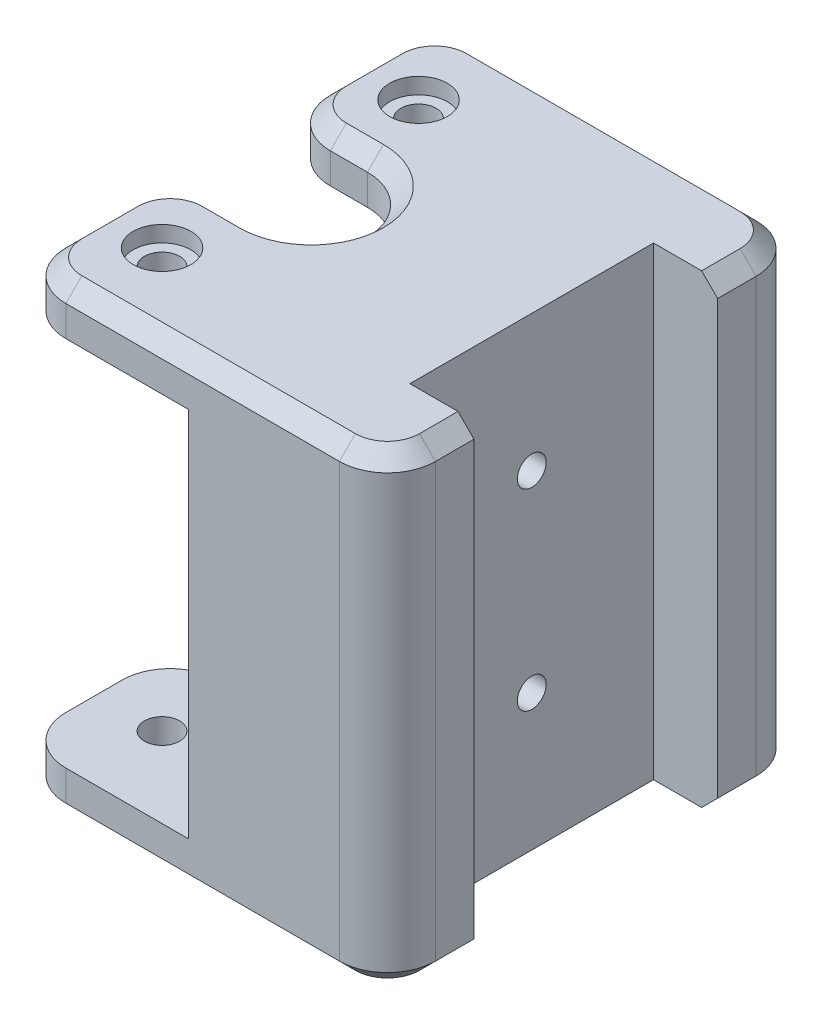
SolidWorks part; units mm, degrees
ref_plane "Спереди" through (0, 0, 0) normal (0, 0, 1) x (1, 0, 0)
ref_plane "Сверху" through (0, 0, 0) normal (0, 1, 0) x (1, 0, 0)
ref_plane "Справа" through (0, 0, 0) normal (1, 0, 0) x (0, 0, -1)
sketch "Эскиз2" plane through (0, 0, 0) normal (0, 1, 0) x (1, 0, 0)
  line L0 (23.6854, 8) -> (23.6854, -8) construction
  line L2 (19.6854, 13) -> (42.75, 13)
  line L3 (19.6854, 13) -> (19.6854, -13)
  line L4 (19.6854, -13) -> (42.75, -13)
  line L5 (42.75, 13) -> (42.75, -13)
  line L6 (19.6854, 13) -> (42.75, -13) construction
  line L7 (19.6854, -13) -> (42.75, 13) construction
  circle A0 centre (0, 0) radius 25 construction
  circle A1 centre (23.6854, 8) radius 1.1
  circle A2 centre (23.6854, -8) radius 1.1
  point P7 (31.2177, 0)
  dimension "D1" = 50
  dimension "D3" = 2.2
  dimension "D4" = 2.2
  dimension "D2" = 16
  dimension "D5" = 4
  dimension "D6" = 42.75
  dimension "D7" = 26
extrude "Бобышка-Вытянуть1" add sketch "Эскиз2" along normal mid plane 29
sketch "Эскиз3" plane through (0, 0, 0) normal (0, 1, 0) x (1, 0, 0)
  circle A0 centre (0, 0) radius 33
  dimension "D1" = 66
extrude "Вырез-Вытянуть1" cut sketch "Эскиз3" against normal mid plane 23.2
sketch "Эскиз4" plane through (0, 14.5, 0) normal (0, 1, 0) x (1, 0, 0)
  line L0 (25, 3.5) -> (19.6854, 3.5)
  line L1 (19.6854, 13) -> (19.6854, -13) construction
  line L2 (19.6854, 3.5) -> (19.6854, -3.5)
  line L3 (19.6854, -3.5) -> (25, -3.5)
  circle A0 centre (0, 0) radius 25 construction
  circle A1 centre (25, 0) radius 3.5
  line M6 (19.6854, 13) -> (19.6854, -13)
  dimension "D1" = 7
extrude "Вырез-Вытянуть2" cut sketch "Эскиз4" against normal through all contours A1 | A1 L0 L3 M6
sketch "Эскиз5" plane through (42.75, 0, 0) normal (1, 0, 0) x (0, 0, -1)
  line L0 (-13, -14.5) -> (13, -14.5) construction
  line L1 (-7.6, 14.5) -> (7.6, 14.5)
  line L2 (-7.6, 14.5) -> (-7.6, -14.5)
  line L3 (-7.6, -14.5) -> (7.6, -14.5)
  line L4 (7.6, 14.5) -> (7.6, -14.5)
  line L5 (-7.6, 14.5) -> (7.6, -14.5) construction
  line L6 (-7.6, -14.5) -> (7.6, 14.5) construction
  point P0 (0, 0)
  dimension "D1" = 15.2
extrude "Вырез-Вытянуть3" cut sketch "Эскиз5" against normal blind 4
fillet "Скругление1" radius 3 10 edges at (42.75, 0, -13) (19.6854, -13.05, -13) (19.6854, -13.05, -3.5) (19.6854, -13.05, 3.5) (19.6854, -13.05, 13) (19.6854, 13.05, -13) (19.6854, 13.05, -3.5) (19.6854, 13.05, 3.5) (19.6854, 13.05, 13) (42.75, 0, 13)
sketch "Эскиз6" plane through (38.75, 0, 0) normal (1, 0, 0) x (0, 0, -1)
  line L0 (-7.6, 0) -> (7.6, 0) construction
  line L1 (-7.6, 14.5) -> (-7.6, -14.5) construction
  line L2 (7.6, -14.5) -> (7.6, 14.5) construction
  circle A0 centre (0, 6) radius 0.9
  circle A1 centre (0, -6) radius 0.9
  point P12 (0, 0)
  dimension "D2" = 1.8
  dimension "D1" = 12
extrude "Вырез-Вытянуть4" cut sketch "Эскиз6" against normal through all
chamfer "Фаска1" distance 1 angle 45 30 edges at (42.75, -14.5, -8.8) (41.8713, -14.5, -12.1213) (31.2177, -14.5, -13) (20.5641, -14.5, -12.1213) (19.6854, -14.5, -8.25) (20.5641, -14.5, -4.3787) (23.8427, -14.5, -3.5) (28.5, -14.5, 0) (23.8427, -14.5, 3.5) (20.5641, -14.5, 4.3787) (19.6854, -14.5, 8.25) (42.75, -14.5, 8.8) (20.5641, -14.5, 12.1213) (41.8713, -14.5, 12.1213) (31.2177, -14.5, 13) (42.75, 14.5, -8.8) (41.8713, 14.5, -12.1213) (31.2177, 14.5, -13) (20.5641, 14.5, -12.1213) (19.6854, 14.5, -8.25) (20.5641, 14.5, -4.3787) (23.8427, 14.5, -3.5) (28.5, 14.5, 0) (23.8427, 14.5, 3.5) (20.5641, 14.5, 4.3787) (19.6854, 14.5, 8.25) (42.75, 14.5, 8.8) (20.5641, 14.5, 12.1213) (41.8713, 14.5, 12.1213) (31.2177, 14.5, 13)
sketch "Эскиз7" plane through (0, 14.5, 0) normal (0, 1, 0) x (1, 0, 0)
  circle A0 centre (23.6854, 8) radius 1.8
  circle A1 centre (23.6854, -8) radius 1.8
  dimension "D1" = 3.6
  dimension "D2" = 3.6
extrude "Вырез-Вытянуть5" cut sketch "Эскиз7" against normal blind 1
mirror "Зеркальное отражение1" about plane through (0, 0, 0) normal (0, 1, 0) of "Вырез-Вытянуть5"
equation "\"motor_diameter\"= 30"
equation "\"mm_diameter\"= IIF ( \"motor_diameter\" < 34 , 41 , \"motor_diameter\" + 8 )"
equation "\"upper_shafts_diameter\"= 5"
equation "\"upper_shats_length\"= 180"
equation "\"upper_bearing_d1\"= 10"
equation "\"upper_bearing_d2\"= 5"
equation "\"upper_bearing_h\"= 15"
equation "\"lower_shafts_diameter\"= 5"
equation "\"lower_shafts_length\"= 180"
equation "\"lower_bearing_d1\"= 10"
equation "\"lower_bearing_d2\"= 5"
equation "\"lower_bearing_h\"= 15"
equation "\"print_offset\"= 0.2"
equation "\"bh_screws_d\"= 2"
equation "\"bh_screws_h\"= 20"
equation "\"bh_screws_hh_d\"= 3.4"
equation "\"bh_screws_hh_h\"= 2"
equation "\"bh_nut_d\"= 3.8"
equation "\"bh_nut_h\"= 2"
equation "\"motor_screws_d\"= 3"
equation "\"motor_screws_h\"= 16"
equation "\"motor_screws_hh_d\"= 5.5"
equation "\"motor_screws_hh_h\"= 3"
equation "\"plate_hole_distance\"= 25.4"
equation "\"plate_screws_d\"= 6.5"
equation "\"shafts_diameter\"= IIF ( \"mm_diameter\" < 42 , 42 + 8 , \"mm_diameter\" + 8 )"
equation "\"central_hole_diameter\"= 8"
equation "\"bh_thikness\"= 4"
equation "\"ends_screws_d\"= 4"
equation "\"ends_screws_h\"= 16"
equation "\"ends_screws_hh_d\"= 6.7"
equation "\"ends_screws_hh_h\"= 4.1"
equation "\"ends_nut_d\"= 6.8"
equation "\"ends_nut_h\"= 3"
equation "\"system_radius\" = ( \"shafts_diameter\" + 12 + \"bh_thikness\" / 2 ) / 2"
equation "\"encoder_distance\"= \"system_radius\" + 4"
equation "\"tape_position\"= \"encoder_distance\" - 2 + 3.9 + 1.7 / 2"
equation "\"D1@Эскиз2\"=\"shafts_diameter\""
equation "\"D3@Эскиз2\"=\"bh_screws_d\"+\"print_offset\""
equation "\"D4@Эскиз2\"=\"D3@Эскиз2\""
equation "\"D5@Эскиз2\"=\"bh_thikness\""
equation "\"D6@Эскиз2\"=\"tape_position\"+4"
equation "\"D1@Бобышка-Вытянуть1\"=\"lower_bearing_h\"+\"bh_thikness\"*2+6"
equation "\"D1@Эскиз3\"=\"system_radius\"*2+2"
equation "\"D1@Вырез-Вытянуть1\"=\"lower_bearing_h\"+\"bh_thikness\"*2+\"print_offset\""
equation "\"D1@Эскиз4\"=\"lower_shafts_diameter\"+2"
equation "\"D1@Эскиз5\"=\"print_offset\"+15"
equation "\"D2@Эскиз6\"=\"bh_screws_d\"-\"print_offset\""
equation "\"D1@Эскиз7\"=\"bh_screws_hh_d\"+\"print_offset\""
equation "\"D2@Эскиз7\"=\"D1@Эскиз7\""
